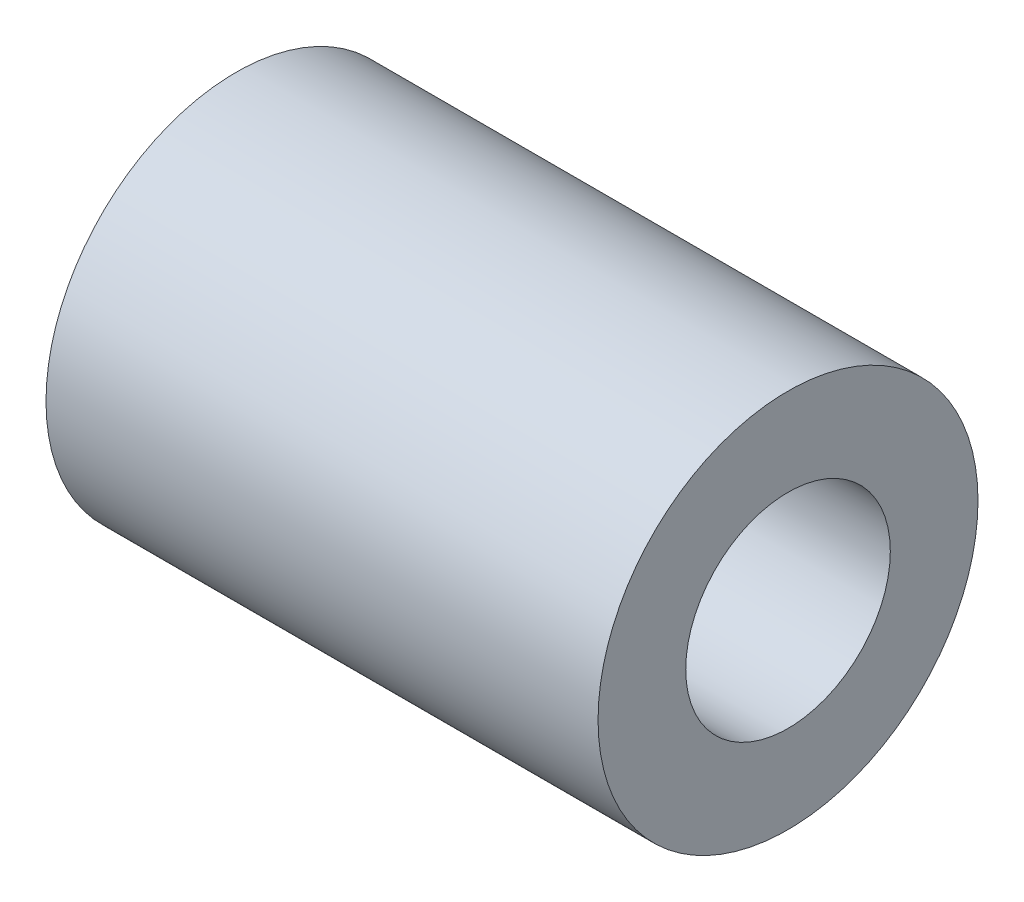
SolidWorks part; units mm, degrees
ref_plane "Front Plane" through (0, 0, 0) normal (0, 0, 1) x (1, 0, 0)
ref_plane "Top Plane" through (0, 0, 0) normal (0, 1, 0) x (1, 0, 0)
ref_plane "Right Plane" through (0, 0, 0) normal (1, 0, 0) x (0, 0, -1)
sketch "Sketch1" plane through (0, 0, 0) normal (1, 0, 0) x (0, 0, -1)
  circle A0 centre (0, 0) radius 3.15
  circle A1 centre (0, 0) radius 5.85
  dimension "D1" = 6.3
  dimension "D2" = 11.7
extrude "Boss-Extrude1" add sketch "Sketch1" along normal blind 17
